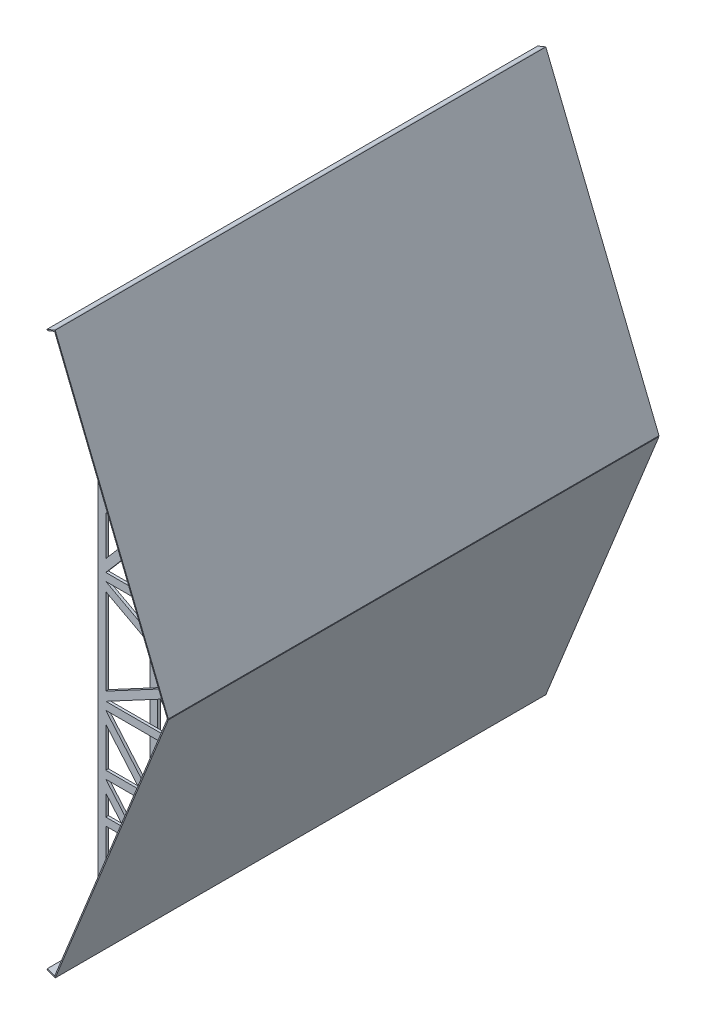
SolidWorks part; units mm, degrees
ref_plane "Спереди" through (0, 0, 0) normal (0, 0, 1) x (1, 0, 0)
ref_plane "Сверху" through (0, 0, 0) normal (0, 1, 0) x (1, 0, 0)
ref_plane "Справа" through (0, 0, 0) normal (1, 0, 0) x (0, 0, -1)
sketch "Эскиз1" plane through (0, 0, 0) normal (0, 0, 1) x (1, 0, 0)
  line L0 (200, -50) -> (200, -9327.9091) construction
  line L1 (200, -4688.9545) -> (2074.2593, -4688.9545) construction
  line L2 (200, -9327.9091) -> (2074.2593, -4688.9545) construction
  line L3 (2074.2593, -4688.9545) -> (200, -50) construction
  line L4 (200, -50) -> (200, -9327.9091)
  line L6 (350, -8956.646) -> (350, -7770.0919)
  line L8 (200, -9327.9091) -> (-82.8184, -10027.9091)
  line L9 (-82.8184, -10027.9091) -> (56.2592, -10084.1001)
  line L10 (56.2592, -10084.1001) -> (2236.0395, -4688.9545)
  line L11 (350, -5688.9545) -> (1670.2331, -5688.9545)
  line L12 (350, -5838.9545) -> (1609.6291, -5838.9545)
  line L13 (350, -5838.9545) -> (1205.6029, -6838.9545)
  line L14 (350, -6069.6824) -> (1008.1915, -6838.9545)
  line L15 (1008.1915, -6838.9545) -> (350, -6838.9545)
  line L16 (1205.6029, -6838.9545) -> (1008.1915, -6838.9545) construction
  line L17 (350, -5518.873) -> (350, -3859.0361)
  line L18 (350, -6069.6824) -> (350, -5838.9545) construction
  line L19 (350, -5838.9545) -> (350, -5688.9545) construction
  line L20 (1609.6291, -5838.9545) -> (1205.6029, -6838.9545)
  line L21 (350, -6988.9545) -> (1144.999, -6988.9545)
  line L22 (350, -6988.9545) -> (890.0029, -7620.0919)
  line L23 (350, -7219.6824) -> (692.5915, -7620.0919)
  line L24 (692.5915, -7620.0919) -> (350, -7620.0919)
  line L25 (350, -7770.0919) -> (829.399, -7770.0919)
  line L26 (890.0029, -7620.0919) -> (692.5915, -7620.0919) construction
  line L27 (692.5915, -7620.0919) -> (826.6832, -7776.8137) construction
  line L28 (350, -7620.0919) -> (350, -7219.6824)
  line L29 (350, -7770.0919) -> (350, -7620.0919) construction
  line L30 (829.399, -7770.0919) -> (350, -8956.646)
  line L31 (1144.999, -6988.9545) -> (890.0029, -7620.0919)
  line L32 (1670.2331, -5688.9545) -> (2033.8567, -4788.9545)
  line L33 (350, -6838.9545) -> (350, -6069.6824)
  line L34 (350, -6988.9545) -> (350, -6838.9545) construction
  line L35 (350, -7219.6824) -> (350, -6988.9545) construction
  line L36 (350, -4688.9545) -> (350, -421.263) construction
  line L37 (200, -50) -> (-82.8184, 650)
  line L38 (-82.8184, 650) -> (56.2592, 706.191)
  line L39 (56.2592, 706.191) -> (2236.0395, -4688.9545)
  line L40 (350, -1607.8172) -> (829.399, -1607.8172)
  line L41 (350, -421.263) -> (350, -1607.8172)
  line L42 (829.399, -1607.8172) -> (350, -421.263)
  line L43 (350, -2158.2267) -> (692.5915, -1757.8172)
  line L44 (350, -1757.8172) -> (350, -2158.2267)
  line L45 (692.5915, -1757.8172) -> (350, -1757.8172)
  line L47 (350, -2388.9545) -> (890.0029, -1757.8172)
  line L48 (1144.999, -2388.9545) -> (890.0029, -1757.8172)
  line L49 (350, -2538.9545) -> (350, -3308.2267)
  line L50 (1008.1915, -2538.9545) -> (350, -2538.9545)
  line L51 (350, -3308.2267) -> (1008.1915, -2538.9545)
  line L52 (350, -3538.9545) -> (1609.6291, -3538.9545)
  line L53 (350, -3538.9545) -> (1205.6029, -2538.9545)
  line L54 (1609.6291, -3538.9545) -> (1205.6029, -2538.9545)
  line L55 (1670.2331, -3688.9545) -> (2033.8567, -4588.9545)
  line L56 (350, -3688.9545) -> (1670.2331, -3688.9545)
  line L57 (200, -9327.9091) -> (-3010.1787, -9327.9091) construction
  line L58 (350, -3688.9545) -> (2033.8567, -4588.9545)
  line L59 (350, -5688.9545) -> (2033.8567, -4788.9545)
  line L60 (350, -3859.0361) -> (1902.7375, -4688.9545)
  line L61 (1902.7375, -4688.9545) -> (350, -5518.873)
  line L62 (350, -3859.0361) -> (350, -3688.9545) construction
  line L63 (350, -5688.9545) -> (350, -5518.873) construction
  line L64 (2033.8567, -4588.9545) -> (2074.2593, -4688.9545) construction
  line L65 (2033.8567, -4788.9545) -> (2074.2593, -4688.9545) construction
  line L66 (350, -2388.9545) -> (1144.999, -2388.9545)
  dimension "D1" = 22
  dimension "D2" = 1874.2593
  dimension "D3" = 150
  dimension "D4" = 150
  dimension "D5" = 150
  dimension "D6" = 1000
  dimension "D7" = 150
  dimension "D8" = 1000
  dimension "D9" = 150
  dimension "D10" = 150
  dimension "D11" = 150
  dimension "D12" = 700
  dimension "D13" = 150
  dimension "D14" = 200
  dimension "D15" = 1724.2593
extrude "Бобышка-Вытянуть1" add sketch "Эскиз1" against normal blind 50
sketch "Эскиз3" plane through (0, 0, 0) normal (1, 0, 0) x (0, 0, -1)
  line L0 (0, 0) -> (8027, 0) construction
  dimension "D1" = 8027
pattern_linear "Линейный массив1" count 9 spacing 1000.25 along (0, 0, -1) of bodies 101
sketch "Эскиз4" plane through (3550.8666, -1434.6432, 0) normal (0.9272, -0.3746, 0) x (0, 0, -1)
  line L0 (50, -9328.7397) -> (0, -9328.7397) construction
  line L1 (-700, -3509.8878) -> (8752, -3509.8878)
  line L2 (-700, -3509.8878) -> (-700, -9329.7397)
  line L3 (-700, -9329.7397) -> (8752, -9329.7397)
  line L4 (8752, -3509.8878) -> (8752, -9329.7397)
  line L5 (0, -9328.7397) -> (0, -3509.8878) construction
  line L6 (50, -3509.8878) -> (0, -3509.8878) construction
  line L7 (8052, -9328.7397) -> (8052, -3509.8878) construction
  dimension "D1" = 1
  dimension "D2" = 700
  dimension "D3" = 700
extrude "Бобышка-Вытянуть2" add sketch "Эскиз4" along normal blind 20 separate body
ref_plane "Плоскость1" through (0, -4688.9545, 0) normal (0, 1, 0) x (1, 0, 0)
sketch "Эскиз5" plane through (-3494.982, -8650.384, 0) normal (-0.3746, -0.9272, 0) x (0.9272, -0.3746, 0)
  line L0 (3679.733, -8052) -> (3679.733, -8002) construction
  line L1 (3829.733, 700) -> (3679.733, 700)
  line L2 (3829.733, 700) -> (3829.733, -8752)
  line L3 (3829.733, -8752) -> (3679.733, -8752)
  line L4 (3679.733, 700) -> (3679.733, -8752)
  point P5 (0, 0)
extrude "Бобышка-Вытянуть3" add sketch "Эскиз5" against normal blind 20 separate body
mirror "Зеркальное отражение2" about plane through (0, -4688.9545, 0) normal (0, 1, 0) of bodies 110 112
